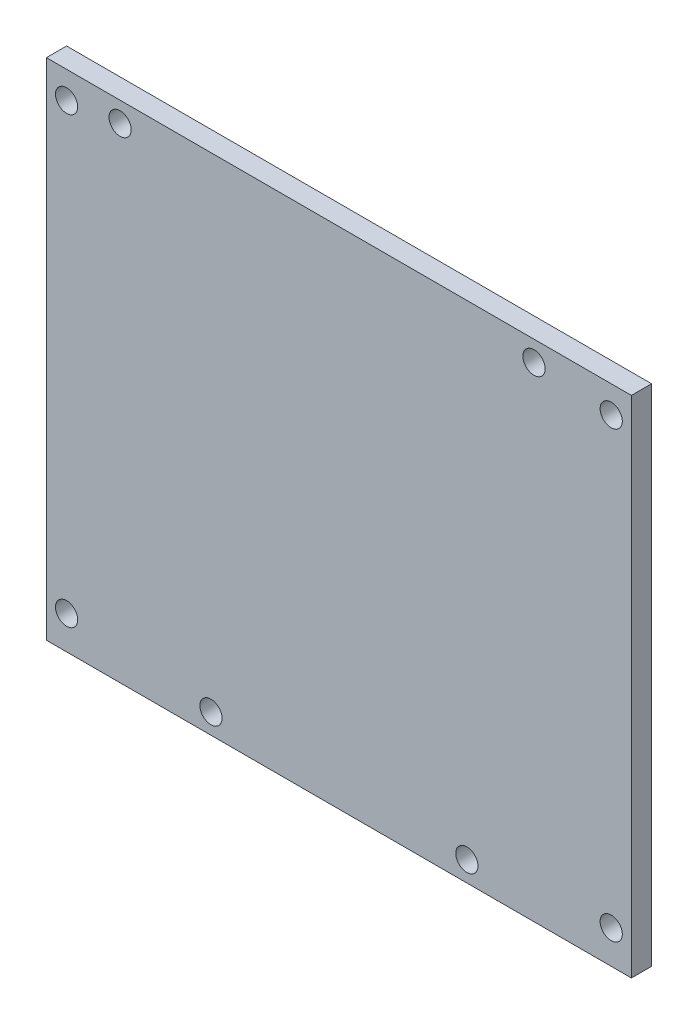
SolidWorks part; units mm, degrees
material "6061-T6 (SS)"
ref_plane "前视基准面" through (0, 0, 0) normal (0, 0, 1) x (1, 0, 0)
ref_plane "上视基准面" through (0, 0, 0) normal (0, 1, 0) x (1, 0, 0)
ref_plane "右视基准面" through (0, 0, 0) normal (1, 0, 0) x (0, 0, -1)
other "Configuration Table"
sketch "草图1" plane through (0, 0, 0) normal (0, 0, 1) x (1, 0, 0)
  line L1 (-4.3, -4.3) -> (53.65, -4.3)
  line L2 (-4.3, -4.3) -> (-4.3, 45.68)
  line L3 (-4.3, 45.68) -> (53.65, 45.68)
  line L4 (53.65, -4.3) -> (53.65, 45.68)
  dimension "D1" = 53.65
  dimension "D2" = 4.3
  dimension "D3" = 45.68
  dimension "D4" = 4.3
extrude "Cover_2mm" add sketch "草图1" along normal blind 2
move or copy body "Stock_Z_Position" bodies to move or copy 106 copy no translate (0, 0, 11.1) parameters "D1"=0, "D2"=0, "D3"=11.1
sketch "草图2" plane through (0, 0, 13.1) normal (0, 0, 1) x (1, 0, 0)
  circle A0 centre (-2.3, -1) radius 1.1
  circle A1 centre (-2.3, 43) radius 1.1
  circle A2 centre (51.65, -1) radius 1.1
  circle A3 centre (51.65, 43) radius 1.1
  circle A4 centre (12, -2.3) radius 1.1
  circle A5 centre (37.35, -2.3) radius 1.1
  circle A6 centre (3, 43.68) radius 1.1
  circle A7 centre (44, 43.68) radius 1.1
  dimension "D1" = 2.2
  dimension "D2" = 3
  dimension "D3" = 12
  dimension "D4" = 37.35
  dimension "D5" = 44
  dimension "D6" = 51.65
  dimension "D7" = 2.3
  dimension "D8" = 43
  dimension "D9" = 43.68
  dimension "D10" = 1
  dimension "D11" = 2.3
extrude "Cover_8xD2p2_Through" cut sketch "草图2" against normal through all
